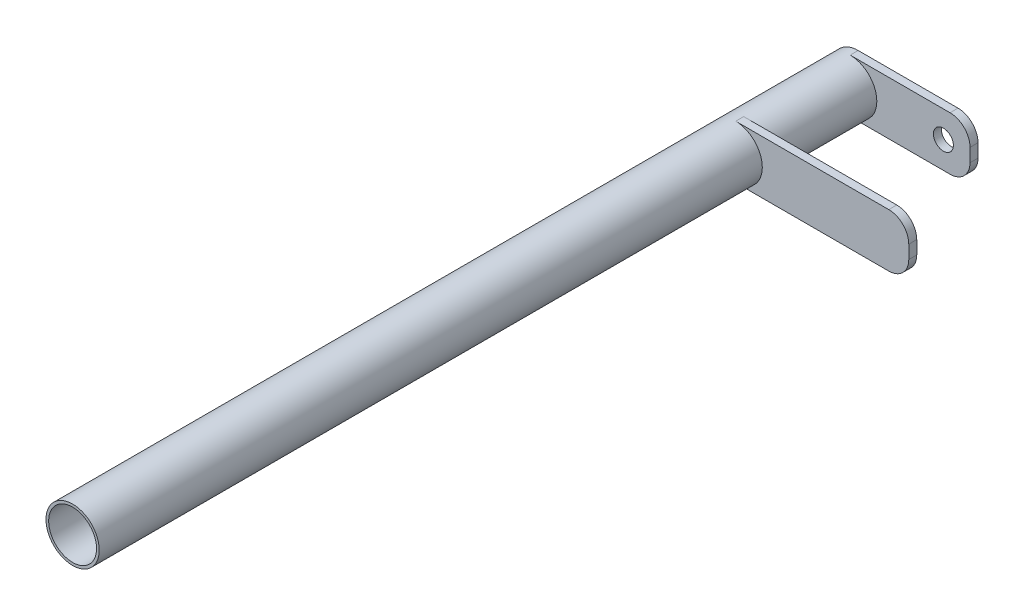
SolidWorks part; units mm, degrees
ref_plane "Plano frontal" through (0, 0, 0) normal (0, 0, 1) x (1, 0, 0)
ref_plane "Plano superior" through (0, 0, 0) normal (0, 1, 0) x (1, 0, 0)
ref_plane "Plano direito" through (0, 0, 0) normal (1, 0, 0) x (0, 0, -1)
sketch "Esboço1" plane through (0, 0, 0) normal (0, 0, 1) x (1, 0, 0)
  circle A0 centre (0, 0) radius 20
  circle A1 centre (0, 0) radius 18
  dimension "D1" = 40
  dimension "D2" = 36
extrude "Ressalto-extrusão1" add sketch "Esboço1" along normal blind 500
sketch "Esboço2" plane through (0, 0, 0) normal (0, 0, -1) x (-1, 0, 0)
  circle A1 centre (0, 0) radius 20
  circle A2 centre (0, 0) radius 18
extrude "Ressalto-extrusão4" add sketch "Esboço2" along normal blind 90
sketch "Esboço4" plane through (0, 0, 0) normal (1, 0, 0) x (0, 0, -1)
  line L0 (90, -20) -> (84, -20)
  line L1 (84, -20) -> (84, 20)
  line L2 (90, 20) -> (-500, 20) construction
  line L3 (84, 20) -> (90, 20)
  line L4 (90, 20) -> (90, -20)
  line L5 (84, -20) -> (4, -20)
  line L6 (-500, -20) -> (90, -20) construction
  line L7 (4, -20) -> (4, 20)
  line L8 (4, 20) -> (-2, 20)
  line L9 (-2, 20) -> (-2, -20)
  line L10 (-2, -20) -> (4, -20)
  dimension "D1" = 6
  dimension "D2" = 80
  dimension "D3" = 6
extrude "Ressalto-extrusão5" add sketch "Esboço4" along normal blind 90 contours L1 L3 L4 L0 | L7 L8 L9 L10
sketch "Esboço5" plane through (0, 0, -90) normal (0, 0, -1) x (-1, 0, 0)
  circle A0 centre (0, 0) radius 18
extrude "Corte-extrusão2" cut sketch "Esboço5" against normal blind 231
sketch "Esboço6" plane through (0, 0, -90) normal (0, 0, -1) x (-1, 0, 0)
  line L0 (-90, 0) -> (-70, 0)
  line L1 (-90, 20) -> (-90, -20) construction
  circle A0 centre (-70, 0) radius 7.5
  dimension "D2" = 15
  dimension "D1" = 20
extrude "Corte-extrusão3" cut sketch "Esboço6" against normal blind 8
sketch "Esboço7" plane through (90, 0, 0) normal (1, 0, 0) x (0, 0, -1)
  line L1 (-2, -20) -> (4, -20)
  line L2 (-2, -20) -> (-2, 20)
  line L3 (-2, 20) -> (4, 20)
  line L4 (4, -20) -> (4, 20)
extrude "Ressalto-extrusão6" add sketch "Esboço7" along normal blind 40
fillet "Filete2" radius 15 2 edges at (90, -20, -87) (90, 20, -87)
fillet "Filete3" radius 15 2 edges at (130, 20, -1) (130, -20, -1)
sketch "Esboço8" plane through (0, 0, 0) normal (1, 0, 0) x (0, 0, -1)
  line L0 (-500, 0) -> (-470, 0)
  line L1 (-500, 18) -> (-500, -18) construction
  circle A0 centre (-470, 0) radius 5
  circle A1 centre (-430, 0) radius 5
  circle A2 centre (-390, 0) radius 5
  circle A3 centre (-350, 0) radius 5
  circle A4 centre (-310, 0) radius 5
  circle A5 centre (-270, 0) radius 5
  circle A6 centre (-230, 0) radius 5
  circle A7 centre (-190, 0) radius 5
  circle A8 centre (-150, 0) radius 5
  circle A9 centre (-110, 0) radius 5
  point P6 (0, 0)
  point P7 (0, 0)
  dimension "D2" = 10
  dimension "D1" = 30
  dimension "D3" = 10
extrude "Corte-extrusão4" cut sketch "Esboço8" against normal blind 40 contours A1 | A0 | A2 | A3 | A4 | A5 | A6 | A7 | A8 | A9
